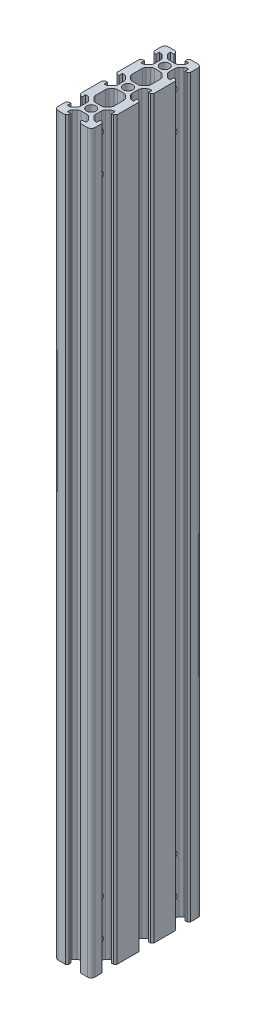
SolidWorks part; units mm, degrees
ref_plane "Front Plane" through (0, 0, 0) normal (0, 0, 1) x (1, 0, 0)
ref_plane "Top Plane" through (0, 0, 0) normal (0, 1, 0) x (1, 0, 0)
ref_plane "Right Plane" through (0, 0, 0) normal (1, 0, 0) x (0, 0, -1)
sketch "Sketch1" plane through (0, 0, 0) normal (0, 1, 0) x (1, 0, 0)
  line B0 (13.1, 59) -> (14.1, 60)
  line B1 (19, 6.9) -> (20, 5.9)
  line B2 (14.4142, 15.8284) -> (13.1236, 14.5379)
  line B3 (20, 14.1) -> (19, 13.1)
  line B4 (15.8284, 5.5858) -> (14.5379, 6.8764)
  line B5 (17.2426, 5) -> (18, 5)
  line B6 (18, 6.9) -> (18, 5)
  line B7 (17.2426, 15) -> (18, 15)
  line B8 (8.2906, 13.9521) -> (11.7094, 13.9521)
  line B9 (18, 15) -> (18, 13.1)
  line B10 (18, 13.1) -> (19, 13.1)
  line B11 (18, 6.9) -> (19, 6.9)
  line B12 (13.9521, 11.7094) -> (13.9521, 8.2906)
  line B13 (6.8764, 14.5379) -> (5.5858, 15.8284)
  line B14 (20, 5.9) -> (20, 2)
  line B15 (14.5379, 13.1236) -> (15.8284, 14.4142)
  line B16 (6.9, 1) -> (5.9, 0)
  line B17 (18, 0) -> (14.1, 0)
  line B18 (14.1, 0) -> (13.1, 1)
  line B19 (5.5858, 4.1716) -> (6.8764, 5.4621)
  line B20 (5, 2.7574) -> (5, 2)
  line B21 (6.9, 2) -> (5, 2)
  line B22 (15, 2.7574) -> (15, 2)
  line B23 (15, 2) -> (13.1, 2)
  line B24 (13.1, 2) -> (13.1, 1)
  line B25 (6.9, 2) -> (6.9, 1)
  line B26 (11.7094, 6.0479) -> (8.2906, 6.0479)
  line B27 (5.9, 0) -> (2, 0)
  line B28 (13.1236, 5.4621) -> (14.4142, 4.1716)
  line B29 (1, 13.1) -> (0, 14.1)
  line B30 (0, 2) -> (0, 5.9)
  line B31 (0, 5.9) -> (1, 6.9)
  line B32 (4.1716, 14.4142) -> (5.4621, 13.1236)
  line B33 (2.7574, 15) -> (2, 15)
  line B34 (2, 13.1) -> (2, 15)
  line B35 (2.7574, 5) -> (2, 5)
  line B36 (2, 5) -> (2, 6.9)
  line B37 (2, 6.9) -> (1, 6.9)
  line B38 (2, 13.1) -> (1, 13.1)
  line B39 (6.0479, 8.2906) -> (6.0479, 11.7094)
  line B40 (5.4621, 6.8764) -> (4.1716, 5.5858)
  circle B41 centre (10, 10) radius 2.5
  arc B42 (5.4621, 13.1236) -> (6.0479, 11.7094) centre (4.0479, 11.7094) cw
  arc B43 (4.1716, 14.4142) -> (2.7574, 15) centre (2.7574, 13) ccw
  arc B44 (5, 17.2426) -> (5.5858, 15.8284) centre (7, 17.2426) ccw
  arc B45 (15, 17.2426) -> (14.4142, 15.8284) centre (13, 17.2426) cw
  arc B46 (17.2426, 15) -> (15.8284, 14.4142) centre (17.2426, 13) ccw
  arc B47 (15.8284, 5.5858) -> (17.2426, 5) centre (17.2426, 7) ccw
  arc B48 (15, 2.7574) -> (14.4142, 4.1716) centre (13, 2.7574) ccw
  arc B49 (5.5858, 4.1716) -> (5, 2.7574) centre (7, 2.7574) ccw
  arc B50 (2.7574, 5) -> (4.1716, 5.5858) centre (2.7574, 7) ccw
  arc B51 (6.0479, 8.2906) -> (5.4621, 6.8764) centre (4.0479, 8.2906) cw
  arc B52 (6.8764, 5.4621) -> (8.2906, 6.0479) centre (8.2906, 4.0479) cw
  arc B53 (11.7094, 6.0479) -> (13.1236, 5.4621) centre (11.7094, 4.0479) cw
  arc B54 (14.5379, 6.8764) -> (13.9521, 8.2906) centre (15.9521, 8.2906) cw
  arc B55 (13.9521, 11.7094) -> (14.5379, 13.1236) centre (15.9521, 11.7094) cw
  arc B56 (11.7094, 13.9521) -> (13.1236, 14.5379) centre (11.7094, 15.9521) ccw
  arc B57 (8.2906, 13.9521) -> (6.8764, 14.5379) centre (8.2906, 15.9521) cw
  arc B58 (2, 0) -> (0, 2) centre (2, 2) cw
  arc B59 (20, 2) -> (18, 0) centre (18, 2) cw
  line B60 (19, 26.9) -> (20, 25.9)
  line B61 (15, 37.2426) -> (15, 42.7574)
  line B62 (14.4142, 35.8284) -> (13.1236, 34.5379)
  line B63 (18, 35) -> (18, 33.1)
  line B64 (20, 45.9) -> (20, 34.1)
  line B65 (0, 25.9) -> (1, 26.9)
  line B66 (17.2426, 25) -> (18, 25)
  line B67 (18, 26.9) -> (19, 26.9)
  line B68 (2, 26.9) -> (1, 26.9)
  line B69 (20, 34.1) -> (19, 33.1)
  line B70 (5, 22.7574) -> (5, 17.2426)
  line B71 (0, 34.1) -> (0, 45.9)
  line B72 (5, 37.2426) -> (5, 42.7574)
  line B73 (13.1236, 25.4621) -> (14.4142, 24.1716)
  line B74 (2, 25) -> (2, 26.9)
  line B75 (6.0479, 28.2906) -> (6.0479, 31.7094)
  line B76 (18, 33.1) -> (19, 33.1)
  line B77 (2, 33.1) -> (2, 35)
  line B78 (18, 26.9) -> (18, 25)
  line B79 (11.7094, 26.0479) -> (8.2906, 26.0479)
  line B80 (17.2426, 35) -> (18, 35)
  line B81 (20, 25.9) -> (20, 14.1)
  line B82 (1, 33.1) -> (0, 34.1)
  line B83 (14.5379, 33.1236) -> (15.8284, 34.4142)
  line B84 (4.1716, 34.4142) -> (5.4621, 33.1236)
  line B85 (13.9521, 31.7094) -> (13.9521, 28.2906)
  line B86 (2.7574, 35) -> (2, 35)
  line B87 (8.2906, 33.9521) -> (11.7094, 33.9521)
  line B88 (5.4621, 26.8764) -> (4.1716, 25.5858)
  line B89 (0, 14.1) -> (0, 25.9)
  line B90 (5.5858, 24.1716) -> (6.8764, 25.4621)
  line B91 (15.8284, 25.5858) -> (14.5379, 26.8764)
  line B92 (6.8764, 34.5379) -> (5.5858, 35.8284)
  line B93 (15, 22.7574) -> (15, 17.2426)
  line B94 (2.7574, 25) -> (2, 25)
  line B95 (2, 33.1) -> (1, 33.1)
  arc B96 (11.7094, 26.0479) -> (13.1236, 25.4621) centre (11.7094, 24.0479) cw
  arc B97 (13.9521, 31.7094) -> (14.5379, 33.1236) centre (15.9521, 31.7094) cw
  arc B98 (14.5379, 26.8764) -> (13.9521, 28.2906) centre (15.9521, 28.2906) cw
  arc B99 (5.5858, 24.1716) -> (5, 22.7574) centre (7, 22.7574) ccw
  arc B100 (5, 37.2426) -> (5.5858, 35.8284) centre (7, 37.2426) ccw
  arc B101 (11.7094, 33.9521) -> (13.1236, 34.5379) centre (11.7094, 35.9521) ccw
  arc B102 (15, 22.7574) -> (14.4142, 24.1716) centre (13, 22.7574) ccw
  arc B103 (2.7574, 25) -> (4.1716, 25.5858) centre (2.7574, 27) ccw
  arc B104 (15, 37.2426) -> (14.4142, 35.8284) centre (13, 37.2426) cw
  circle B105 centre (10, 30) radius 2.5
  arc B106 (8.2906, 33.9521) -> (6.8764, 34.5379) centre (8.2906, 35.9521) cw
  arc B107 (6.0479, 28.2906) -> (5.4621, 26.8764) centre (4.0479, 28.2906) cw
  arc B108 (6.8764, 25.4621) -> (8.2906, 26.0479) centre (8.2906, 24.0479) cw
  arc B109 (4.1716, 34.4142) -> (2.7574, 35) centre (2.7574, 33) ccw
  arc B110 (15.8284, 25.5858) -> (17.2426, 25) centre (17.2426, 27) ccw
  arc B111 (5.4621, 33.1236) -> (6.0479, 31.7094) centre (4.0479, 31.7094) cw
  arc B112 (17.2426, 35) -> (15.8284, 34.4142) centre (17.2426, 33) ccw
  line B113 (18, 55) -> (18, 53.1)
  line B114 (13.9521, 51.7094) -> (13.9521, 48.2906)
  line B115 (5.9, 60) -> (6.9, 59)
  line B116 (5, 57.2426) -> (5, 58)
  line B117 (4.1716, 54.4142) -> (5.4621, 53.1236)
  line B118 (18, 46.9) -> (19, 46.9)
  line B119 (13.1, 58) -> (13.1, 59)
  line B120 (11.7094, 46.0479) -> (8.2906, 46.0479)
  line B121 (2, 46.9) -> (1, 46.9)
  line B122 (6.8764, 54.5379) -> (5.5858, 55.8284)
  line B123 (13.1, 58) -> (15, 58)
  line B124 (2, 53.1) -> (2, 55)
  line B125 (18, 46.9) -> (18, 45)
  line B126 (0, 45.9) -> (1, 46.9)
  line B127 (6.9, 58) -> (6.9, 59)
  line B128 (13.1236, 45.4621) -> (14.4142, 44.1716)
  line B129 (15.8284, 45.5858) -> (14.5379, 46.8764)
  line B130 (20, 58) -> (20, 54.1)
  line B131 (2, 45) -> (2, 46.9)
  line B132 (17.2426, 55) -> (18, 55)
  line B133 (5, 58) -> (6.9, 58)
  line B134 (15, 57.2426) -> (15, 58)
  line B135 (2.7574, 45) -> (2, 45)
  line B136 (19, 46.9) -> (20, 45.9)
  line B137 (1, 53.1) -> (0, 54.1)
  line B138 (14.5379, 53.1236) -> (15.8284, 54.4142)
  line B139 (5.5858, 44.1716) -> (6.8764, 45.4621)
  line B140 (14.4142, 55.8284) -> (13.1236, 54.5379)
  line B141 (6.0479, 48.2906) -> (6.0479, 51.7094)
  line B142 (14.1, 60) -> (18, 60)
  line B143 (2, 60) -> (5.9, 60)
  line B144 (20, 54.1) -> (19, 53.1)
  line B145 (8.2906, 53.9521) -> (11.7094, 53.9521)
  line B146 (17.2426, 45) -> (18, 45)
  line B147 (0, 54.1) -> (0, 58)
  line B148 (2.7574, 55) -> (2, 55)
  line B149 (2, 53.1) -> (1, 53.1)
  line B150 (18, 53.1) -> (19, 53.1)
  line B151 (5.4621, 46.8764) -> (4.1716, 45.5858)
  arc B152 (5, 57.2426) -> (5.5858, 55.8284) centre (7, 57.2426) ccw
  arc B153 (2.7574, 45) -> (4.1716, 45.5858) centre (2.7574, 47) ccw
  arc B154 (11.7094, 46.0479) -> (13.1236, 45.4621) centre (11.7094, 44.0479) cw
  arc B155 (5.5858, 44.1716) -> (5, 42.7574) centre (7, 42.7574) ccw
  arc B156 (11.7094, 53.9521) -> (13.1236, 54.5379) centre (11.7094, 55.9521) ccw
  circle B157 centre (10, 50) radius 2.5
  arc B158 (0, 58) -> (2, 60) centre (2, 58) cw
  arc B159 (14.5379, 46.8764) -> (13.9521, 48.2906) centre (15.9521, 48.2906) cw
  arc B160 (6.8764, 45.4621) -> (8.2906, 46.0479) centre (8.2906, 44.0479) cw
  arc B161 (15, 57.2426) -> (14.4142, 55.8284) centre (13, 57.2426) cw
  arc B162 (15, 42.7574) -> (14.4142, 44.1716) centre (13, 42.7574) ccw
  arc B163 (5.4621, 53.1236) -> (6.0479, 51.7094) centre (4.0479, 51.7094) cw
  arc B164 (18, 60) -> (20, 58) centre (18, 58) cw
  arc B165 (6.0479, 48.2906) -> (5.4621, 46.8764) centre (4.0479, 48.2906) cw
  arc B166 (13.9521, 51.7094) -> (14.5379, 53.1236) centre (15.9521, 51.7094) cw
  arc B167 (4.1716, 54.4142) -> (2.7574, 55) centre (2.7574, 53) ccw
  arc B168 (8.2906, 53.9521) -> (6.8764, 54.5379) centre (8.2906, 55.9521) cw
  arc B169 (15.8284, 45.5858) -> (17.2426, 45) centre (17.2426, 47) ccw
  arc B170 (17.2426, 55) -> (15.8284, 54.4142) centre (17.2426, 53) ccw
sketch_block_instance "2060-1"
sketch_block "2060" parameters "D1"=2, "D2"=2, "D3"=2
extrude "Boss-Extrude1" add sketch "Sketch1" along normal blind 400
sketch "Sketch3" plane through (0, 0, 0) normal (-1, 0, 0) x (0, 0, 1)
  line L0 (-50, 400) -> (-50, 390) construction
  line L1 (-51.7094, 400) -> (-48.2906, 400) construction
  line L2 (-10, 400) -> (-10, 390) construction
  line L3 (-11.7094, 400) -> (-8.2906, 400) construction
  line L4 (-50, 390) -> (-50, 370) construction
  line L5 (-10, 390) -> (-10, 370) construction
  line L6 (0, 200) -> (53.5094, 200) construction
  line L7 (0, 400) -> (0, 0) construction
  line L8 (-10, 10) -> (-10, 30) construction
  line L9 (-50, 10) -> (-50, 30) construction
  line L10 (-10, 0) -> (-10, 10) construction
  line L11 (-50, 0) -> (-50, 10) construction
  circle A0 centre (-50, 390) radius 2.5
  circle A1 centre (-10, 390) radius 2.5
  circle A2 centre (-50, 370) radius 2.5
  circle A3 centre (-10, 370) radius 2.5
  circle A4 centre (-10, 30) radius 2.5
  circle A5 centre (-50, 30) radius 2.5
  circle A6 centre (-10, 10) radius 2.5
  circle A7 centre (-50, 10) radius 2.5
extrude "Cut-Extrude1" cut sketch "Sketch3" against normal through all
sketch "Sketch4" plane through (0, 0, 0) normal (-1, 0, 0) x (0, 0, 1)
  line L0 (0, 200) -> (53.5094, 200) construction
  line L1 (0, 200) -> (53.5094, 200) construction
  circle A0 centre (-50, 390) radius 5
  circle A1 centre (-50, 370) radius 5
  circle A2 centre (-10, 390) radius 5
  circle A3 centre (-10, 370) radius 5
  circle A4 centre (-10, 30) radius 5
  circle A5 centre (-10, 10) radius 5
  circle A6 centre (-50, 30) radius 5
  circle A7 centre (-50, 10) radius 5
sketch "Sketch5" plane through (0, 400, 0) normal (0, 1, 0) x (1, 0, 0)
  line B0 (13.1, 59) -> (14.1, 60)
  line B1 (19, 6.9) -> (20, 5.9)
  line B2 (14.4142, 15.8284) -> (13.1236, 14.5379)
  line B3 (20, 14.1) -> (19, 13.1)
  line B4 (15.8284, 5.5858) -> (14.5379, 6.8764)
  line B5 (17.2426, 5) -> (18, 5)
  line B6 (18, 6.9) -> (18, 5)
  line B7 (17.2426, 15) -> (18, 15)
  line B8 (8.2906, 13.9521) -> (11.7094, 13.9521)
  line B9 (18, 15) -> (18, 13.1)
  line B10 (18, 13.1) -> (19, 13.1)
  line B11 (18, 6.9) -> (19, 6.9)
  line B12 (13.9521, 11.7094) -> (13.9521, 8.2906)
  line B13 (6.8764, 14.5379) -> (5.5858, 15.8284)
  line B14 (20, 5.9) -> (20, 2)
  line B15 (14.5379, 13.1236) -> (15.8284, 14.4142)
  line B16 (6.9, 1) -> (5.9, 0)
  line B17 (18, 0) -> (14.1, 0)
  line B18 (14.1, 0) -> (13.1, 1)
  line B19 (5.5858, 4.1716) -> (6.8764, 5.4621)
  line B20 (5, 2.7574) -> (5, 2)
  line B21 (6.9, 2) -> (5, 2)
  line B22 (15, 2.7574) -> (15, 2)
  line B23 (15, 2) -> (13.1, 2)
  line B24 (13.1, 2) -> (13.1, 1)
  line B25 (6.9, 2) -> (6.9, 1)
  line B26 (11.7094, 6.0479) -> (8.2906, 6.0479)
  line B27 (5.9, 0) -> (2, 0)
  line B28 (13.1236, 5.4621) -> (14.4142, 4.1716)
  line B29 (1, 13.1) -> (0, 14.1)
  line B30 (0, 2) -> (0, 5.9)
  line B31 (0, 5.9) -> (1, 6.9)
  line B32 (4.1716, 14.4142) -> (5.4621, 13.1236)
  line B33 (2.7574, 15) -> (2, 15)
  line B34 (2, 13.1) -> (2, 15)
  line B35 (2.7574, 5) -> (2, 5)
  line B36 (2, 5) -> (2, 6.9)
  line B37 (2, 6.9) -> (1, 6.9)
  line B38 (2, 13.1) -> (1, 13.1)
  line B39 (6.0479, 8.2906) -> (6.0479, 11.7094)
  line B40 (5.4621, 6.8764) -> (4.1716, 5.5858)
  circle B41 centre (10, 10) radius 2.5
  arc B42 (5.4621, 13.1236) -> (6.0479, 11.7094) centre (4.0479, 11.7094) cw
  arc B43 (4.1716, 14.4142) -> (2.7574, 15) centre (2.7574, 13) ccw
  arc B44 (5, 17.2426) -> (5.5858, 15.8284) centre (7, 17.2426) ccw
  arc B45 (15, 17.2426) -> (14.4142, 15.8284) centre (13, 17.2426) cw
  arc B46 (17.2426, 15) -> (15.8284, 14.4142) centre (17.2426, 13) ccw
  arc B47 (15.8284, 5.5858) -> (17.2426, 5) centre (17.2426, 7) ccw
  arc B48 (15, 2.7574) -> (14.4142, 4.1716) centre (13, 2.7574) ccw
  arc B49 (5.5858, 4.1716) -> (5, 2.7574) centre (7, 2.7574) ccw
  arc B50 (2.7574, 5) -> (4.1716, 5.5858) centre (2.7574, 7) ccw
  arc B51 (6.0479, 8.2906) -> (5.4621, 6.8764) centre (4.0479, 8.2906) cw
  arc B52 (6.8764, 5.4621) -> (8.2906, 6.0479) centre (8.2906, 4.0479) cw
  arc B53 (11.7094, 6.0479) -> (13.1236, 5.4621) centre (11.7094, 4.0479) cw
  arc B54 (14.5379, 6.8764) -> (13.9521, 8.2906) centre (15.9521, 8.2906) cw
  arc B55 (13.9521, 11.7094) -> (14.5379, 13.1236) centre (15.9521, 11.7094) cw
  arc B56 (11.7094, 13.9521) -> (13.1236, 14.5379) centre (11.7094, 15.9521) ccw
  arc B57 (8.2906, 13.9521) -> (6.8764, 14.5379) centre (8.2906, 15.9521) cw
  arc B58 (2, 0) -> (0, 2) centre (2, 2) cw
  arc B59 (20, 2) -> (18, 0) centre (18, 2) cw
  line B60 (19, 26.9) -> (20, 25.9)
  line B61 (15, 37.2426) -> (15, 42.7574)
  line B62 (14.4142, 35.8284) -> (13.1236, 34.5379)
  line B63 (18, 35) -> (18, 33.1)
  line B64 (20, 45.9) -> (20, 34.1)
  line B65 (0, 25.9) -> (1, 26.9)
  line B66 (17.2426, 25) -> (18, 25)
  line B67 (18, 26.9) -> (19, 26.9)
  line B68 (2, 26.9) -> (1, 26.9)
  line B69 (20, 34.1) -> (19, 33.1)
  line B70 (5, 22.7574) -> (5, 17.2426)
  line B71 (0, 34.1) -> (0, 45.9)
  line B72 (5, 37.2426) -> (5, 42.7574)
  line B73 (13.1236, 25.4621) -> (14.4142, 24.1716)
  line B74 (2, 25) -> (2, 26.9)
  line B75 (6.0479, 28.2906) -> (6.0479, 31.7094)
  line B76 (18, 33.1) -> (19, 33.1)
  line B77 (2, 33.1) -> (2, 35)
  line B78 (18, 26.9) -> (18, 25)
  line B79 (11.7094, 26.0479) -> (8.2906, 26.0479)
  line B80 (17.2426, 35) -> (18, 35)
  line B81 (20, 25.9) -> (20, 14.1)
  line B82 (1, 33.1) -> (0, 34.1)
  line B83 (14.5379, 33.1236) -> (15.8284, 34.4142)
  line B84 (4.1716, 34.4142) -> (5.4621, 33.1236)
  line B85 (13.9521, 31.7094) -> (13.9521, 28.2906)
  line B86 (2.7574, 35) -> (2, 35)
  line B87 (8.2906, 33.9521) -> (11.7094, 33.9521)
  line B88 (5.4621, 26.8764) -> (4.1716, 25.5858)
  line B89 (0, 14.1) -> (0, 25.9)
  line B90 (5.5858, 24.1716) -> (6.8764, 25.4621)
  line B91 (15.8284, 25.5858) -> (14.5379, 26.8764)
  line B92 (6.8764, 34.5379) -> (5.5858, 35.8284)
  line B93 (15, 22.7574) -> (15, 17.2426)
  line B94 (2.7574, 25) -> (2, 25)
  line B95 (2, 33.1) -> (1, 33.1)
  arc B96 (11.7094, 26.0479) -> (13.1236, 25.4621) centre (11.7094, 24.0479) cw
  arc B97 (13.9521, 31.7094) -> (14.5379, 33.1236) centre (15.9521, 31.7094) cw
  arc B98 (14.5379, 26.8764) -> (13.9521, 28.2906) centre (15.9521, 28.2906) cw
  arc B99 (5.5858, 24.1716) -> (5, 22.7574) centre (7, 22.7574) ccw
  arc B100 (5, 37.2426) -> (5.5858, 35.8284) centre (7, 37.2426) ccw
  arc B101 (11.7094, 33.9521) -> (13.1236, 34.5379) centre (11.7094, 35.9521) ccw
  arc B102 (15, 22.7574) -> (14.4142, 24.1716) centre (13, 22.7574) ccw
  arc B103 (2.7574, 25) -> (4.1716, 25.5858) centre (2.7574, 27) ccw
  arc B104 (15, 37.2426) -> (14.4142, 35.8284) centre (13, 37.2426) cw
  circle B105 centre (10, 30) radius 2.5
  arc B106 (8.2906, 33.9521) -> (6.8764, 34.5379) centre (8.2906, 35.9521) cw
  arc B107 (6.0479, 28.2906) -> (5.4621, 26.8764) centre (4.0479, 28.2906) cw
  arc B108 (6.8764, 25.4621) -> (8.2906, 26.0479) centre (8.2906, 24.0479) cw
  arc B109 (4.1716, 34.4142) -> (2.7574, 35) centre (2.7574, 33) ccw
  arc B110 (15.8284, 25.5858) -> (17.2426, 25) centre (17.2426, 27) ccw
  arc B111 (5.4621, 33.1236) -> (6.0479, 31.7094) centre (4.0479, 31.7094) cw
  arc B112 (17.2426, 35) -> (15.8284, 34.4142) centre (17.2426, 33) ccw
  line B113 (18, 55) -> (18, 53.1)
  line B114 (13.9521, 51.7094) -> (13.9521, 48.2906)
  line B115 (5.9, 60) -> (6.9, 59)
  line B116 (5, 57.2426) -> (5, 58)
  line B117 (4.1716, 54.4142) -> (5.4621, 53.1236)
  line B118 (18, 46.9) -> (19, 46.9)
  line B119 (13.1, 58) -> (13.1, 59)
  line B120 (11.7094, 46.0479) -> (8.2906, 46.0479)
  line B121 (2, 46.9) -> (1, 46.9)
  line B122 (6.8764, 54.5379) -> (5.5858, 55.8284)
  line B123 (13.1, 58) -> (15, 58)
  line B124 (2, 53.1) -> (2, 55)
  line B125 (18, 46.9) -> (18, 45)
  line B126 (0, 45.9) -> (1, 46.9)
  line B127 (6.9, 58) -> (6.9, 59)
  line B128 (13.1236, 45.4621) -> (14.4142, 44.1716)
  line B129 (15.8284, 45.5858) -> (14.5379, 46.8764)
  line B130 (20, 58) -> (20, 54.1)
  line B131 (2, 45) -> (2, 46.9)
  line B132 (17.2426, 55) -> (18, 55)
  line B133 (5, 58) -> (6.9, 58)
  line B134 (15, 57.2426) -> (15, 58)
  line B135 (2.7574, 45) -> (2, 45)
  line B136 (19, 46.9) -> (20, 45.9)
  line B137 (1, 53.1) -> (0, 54.1)
  line B138 (14.5379, 53.1236) -> (15.8284, 54.4142)
  line B139 (5.5858, 44.1716) -> (6.8764, 45.4621)
  line B140 (14.4142, 55.8284) -> (13.1236, 54.5379)
  line B141 (6.0479, 48.2906) -> (6.0479, 51.7094)
  line B142 (14.1, 60) -> (18, 60)
  line B143 (2, 60) -> (5.9, 60)
  line B144 (20, 54.1) -> (19, 53.1)
  line B145 (8.2906, 53.9521) -> (11.7094, 53.9521)
  line B146 (17.2426, 45) -> (18, 45)
  line B147 (0, 54.1) -> (0, 58)
  line B148 (2.7574, 55) -> (2, 55)
  line B149 (2, 53.1) -> (1, 53.1)
  line B150 (18, 53.1) -> (19, 53.1)
  line B151 (5.4621, 46.8764) -> (4.1716, 45.5858)
  arc B152 (5, 57.2426) -> (5.5858, 55.8284) centre (7, 57.2426) ccw
  arc B153 (2.7574, 45) -> (4.1716, 45.5858) centre (2.7574, 47) ccw
  arc B154 (11.7094, 46.0479) -> (13.1236, 45.4621) centre (11.7094, 44.0479) cw
  arc B155 (5.5858, 44.1716) -> (5, 42.7574) centre (7, 42.7574) ccw
  arc B156 (11.7094, 53.9521) -> (13.1236, 54.5379) centre (11.7094, 55.9521) ccw
  circle B157 centre (10, 50) radius 2.5
  arc B158 (0, 58) -> (2, 60) centre (2, 58) cw
  arc B159 (14.5379, 46.8764) -> (13.9521, 48.2906) centre (15.9521, 48.2906) cw
  arc B160 (6.8764, 45.4621) -> (8.2906, 46.0479) centre (8.2906, 44.0479) cw
  arc B161 (15, 57.2426) -> (14.4142, 55.8284) centre (13, 57.2426) cw
  arc B162 (15, 42.7574) -> (14.4142, 44.1716) centre (13, 42.7574) ccw
  arc B163 (5.4621, 53.1236) -> (6.0479, 51.7094) centre (4.0479, 51.7094) cw
  arc B164 (18, 60) -> (20, 58) centre (18, 58) cw
  arc B165 (6.0479, 48.2906) -> (5.4621, 46.8764) centre (4.0479, 48.2906) cw
  arc B166 (13.9521, 51.7094) -> (14.5379, 53.1236) centre (15.9521, 51.7094) cw
  arc B167 (4.1716, 54.4142) -> (2.7574, 55) centre (2.7574, 53) ccw
  arc B168 (8.2906, 53.9521) -> (6.8764, 54.5379) centre (8.2906, 55.9521) cw
  arc B169 (15.8284, 45.5858) -> (17.2426, 45) centre (17.2426, 47) ccw
  arc B170 (17.2426, 55) -> (15.8284, 54.4142) centre (17.2426, 53) ccw
sketch_block_instance "2060-2"
sketch "Sketch6" plane through (0, 0, 0) normal (0, -1, 0) x (1, 0, 0)
  line L0 (5, -22.7574) -> (5, -17.2426) construction
  line L1 (6.8764, -14.5379) -> (5.5858, -15.8284) construction
  line L2 (8.2906, -13.9521) -> (11.7094, -13.9521) construction
  line L3 (14.4142, -15.8284) -> (13.1236, -14.5379) construction
  line L4 (15, -22.7574) -> (15, -17.2426) construction
  line L5 (13.1236, -25.4621) -> (14.4142, -24.1716) construction
  line L6 (11.7094, -26.0479) -> (8.2906, -26.0479) construction
  line L7 (5.5858, -24.1716) -> (6.8764, -25.4621) construction
  line L8 (11.7094, -46.0479) -> (8.2906, -46.0479) construction
  line L9 (5.5858, -44.1716) -> (6.8764, -45.4621) construction
  line L10 (5, -37.2426) -> (5, -42.7574) construction
  line L11 (6.8764, -34.5379) -> (5.5858, -35.8284) construction
  line L12 (8.2906, -33.9521) -> (11.7094, -33.9521) construction
  line L13 (14.4142, -35.8284) -> (13.1236, -34.5379) construction
  line L14 (15, -37.2426) -> (15, -42.7574) construction
  line L15 (13.1236, -45.4621) -> (14.4142, -44.1716) construction
  line L16 (13.9521, -51.7094) -> (13.9521, -48.2906) construction
  line L17 (15.8284, -45.5858) -> (14.5379, -46.8764) construction
  line L18 (17.2426, -45) -> (18, -45) construction
  line L19 (18, -46.9) -> (18, -45) construction
  line L20 (18, -46.9) -> (19, -46.9) construction
  line L21 (19, -46.9) -> (20, -45.9) construction
  line L22 (20, -45.9) -> (20, -34.1) construction
  line L23 (20, -34.1) -> (19, -33.1) construction
  line L24 (18, -33.1) -> (19, -33.1) construction
  line L25 (18, -35) -> (18, -33.1) construction
  line L26 (17.2426, -35) -> (18, -35) construction
  line L27 (14.5379, -33.1236) -> (15.8284, -34.4142) construction
  line L28 (13.9521, -31.7094) -> (13.9521, -28.2906) construction
  line L29 (15.8284, -25.5858) -> (14.5379, -26.8764) construction
  line L30 (17.2426, -25) -> (18, -25) construction
  line L31 (18, -26.9) -> (18, -25) construction
  line L32 (18, -26.9) -> (19, -26.9) construction
  line L33 (19, -26.9) -> (20, -25.9) construction
  line L34 (20, -25.9) -> (20, -14.1) construction
  line L35 (20, -14.1) -> (19, -13.1) construction
  line L36 (18, -13.1) -> (19, -13.1) construction
  line L37 (18, -15) -> (18, -13.1) construction
  line L38 (17.2426, -15) -> (18, -15) construction
  line L39 (14.5379, -13.1236) -> (15.8284, -14.4142) construction
  line L40 (13.9521, -11.7094) -> (13.9521, -8.2906) construction
  line L41 (15.8284, -5.5858) -> (14.5379, -6.8764) construction
  line L42 (17.2426, -5) -> (18, -5) construction
  line L43 (18, -6.9) -> (18, -5) construction
  line L44 (18, -6.9) -> (19, -6.9) construction
  line L45 (19, -6.9) -> (20, -5.9) construction
  line L46 (20, -5.9) -> (20, -2) construction
  line L47 (18, 0) -> (14.1, 0) construction
  line L48 (14.1, 0) -> (13.1, -1) construction
  line L49 (13.1, -2) -> (13.1, -1) construction
  line L50 (15, -2) -> (13.1, -2) construction
  line L51 (15, -2.7574) -> (15, -2) construction
  line L52 (13.1236, -5.4621) -> (14.4142, -4.1716) construction
  line L53 (11.7094, -6.0479) -> (8.2906, -6.0479) construction
  line L54 (5.5858, -4.1716) -> (6.8764, -5.4621) construction
  line L55 (5, -2.7574) -> (5, -2) construction
  line L56 (6.9, -2) -> (5, -2) construction
  line L57 (6.9, -2) -> (6.9, -1) construction
  line L58 (6.9, -1) -> (5.9, 0) construction
  line L59 (5.9, 0) -> (2, 0) construction
  line L60 (0, -2) -> (0, -5.9) construction
  line L61 (0, -5.9) -> (1, -6.9) construction
  line L62 (2, -6.9) -> (1, -6.9) construction
  line L63 (2, -5) -> (2, -6.9) construction
  line L64 (2.7574, -5) -> (2, -5) construction
  line L65 (5.4621, -6.8764) -> (4.1716, -5.5858) construction
  line L66 (6.0479, -8.2906) -> (6.0479, -11.7094) construction
  line L67 (4.1716, -14.4142) -> (5.4621, -13.1236) construction
  line L68 (2.7574, -15) -> (2, -15) construction
  line L69 (2, -13.1) -> (2, -15) construction
  line L70 (2, -13.1) -> (1, -13.1) construction
  line L71 (1, -13.1) -> (0, -14.1) construction
  line L72 (0, -14.1) -> (0, -25.9) construction
  line L73 (0, -25.9) -> (1, -26.9) construction
  line L74 (2, -26.9) -> (1, -26.9) construction
  line L75 (2, -25) -> (2, -26.9) construction
  line L76 (2.7574, -25) -> (2, -25) construction
  line L77 (5.4621, -26.8764) -> (4.1716, -25.5858) construction
  line L78 (6.0479, -28.2906) -> (6.0479, -31.7094) construction
  line L79 (4.1716, -34.4142) -> (5.4621, -33.1236) construction
  line L80 (2.7574, -35) -> (2, -35) construction
  line L81 (2, -33.1) -> (2, -35) construction
  line L82 (2, -33.1) -> (1, -33.1) construction
  line L83 (1, -33.1) -> (0, -34.1) construction
  line L84 (0, -34.1) -> (0, -45.9) construction
  line L85 (0, -45.9) -> (1, -46.9) construction
  line L86 (2, -46.9) -> (1, -46.9) construction
  line L87 (2, -45) -> (2, -46.9) construction
  line L88 (2.7574, -45) -> (2, -45) construction
  line L89 (5.4621, -46.8764) -> (4.1716, -45.5858) construction
  line L90 (6.0479, -48.2906) -> (6.0479, -51.7094) construction
  line L91 (4.1716, -54.4142) -> (5.4621, -53.1236) construction
  line L92 (2.7574, -55) -> (2, -55) construction
  line L93 (2, -53.1) -> (2, -55) construction
  line L94 (2, -53.1) -> (1, -53.1) construction
  line L95 (1, -53.1) -> (0, -54.1) construction
  line L96 (0, -54.1) -> (0, -58) construction
  line L97 (2, -60) -> (5.9, -60) construction
  line L98 (5.9, -60) -> (6.9, -59) construction
  line L99 (6.9, -58) -> (6.9, -59) construction
  line L100 (5, -58) -> (6.9, -58) construction
  line L101 (5, -57.2426) -> (5, -58) construction
  line L102 (6.8764, -54.5379) -> (5.5858, -55.8284) construction
  line L103 (8.2906, -53.9521) -> (11.7094, -53.9521) construction
  line L104 (14.4142, -55.8284) -> (13.1236, -54.5379) construction
  line L105 (15, -57.2426) -> (15, -58) construction
  line L106 (13.1, -58) -> (15, -58) construction
  line L107 (13.1, -58) -> (13.1, -59) construction
  line L108 (13.1, -59) -> (14.1, -60) construction
  line L109 (14.1, -60) -> (18, -60) construction
  line L110 (20, -58) -> (20, -54.1) construction
  line L111 (20, -54.1) -> (19, -53.1) construction
  line L112 (18, -53.1) -> (19, -53.1) construction
  line L113 (18, -55) -> (18, -53.1) construction
  line L114 (17.2426, -55) -> (18, -55) construction
  line L115 (14.5379, -53.1236) -> (15.8284, -54.4142) construction
  line L116 (5, -22.7574) -> (5, -17.2426)
  line L117 (6.8764, -14.5379) -> (5.5858, -15.8284)
  line L118 (8.2906, -13.9521) -> (11.7094, -13.9521)
  line L119 (14.4142, -15.8284) -> (13.1236, -14.5379)
  line L120 (15, -22.7574) -> (15, -17.2426)
  line L121 (13.1236, -25.4621) -> (14.4142, -24.1716)
  line L122 (11.7094, -26.0479) -> (8.2906, -26.0479)
  line L123 (5.5858, -24.1716) -> (6.8764, -25.4621)
  line L124 (11.7094, -46.0479) -> (8.2906, -46.0479)
  line L125 (5.5858, -44.1716) -> (6.8764, -45.4621)
  line L126 (5, -37.2426) -> (5, -42.7574)
  line L127 (6.8764, -34.5379) -> (5.5858, -35.8284)
  line L128 (8.2906, -33.9521) -> (11.7094, -33.9521)
  line L129 (14.4142, -35.8284) -> (13.1236, -34.5379)
  line L130 (15, -37.2426) -> (15, -42.7574)
  line L131 (13.1236, -45.4621) -> (14.4142, -44.1716)
  line L132 (13.9521, -51.7094) -> (13.9521, -48.2906)
  line L133 (15.8284, -45.5858) -> (14.5379, -46.8764)
  line L134 (17.2426, -45) -> (18, -45)
  line L135 (18, -46.9) -> (18, -45)
  line L136 (18, -46.9) -> (19, -46.9)
  line L137 (19, -46.9) -> (20, -45.9)
  line L138 (20, -45.9) -> (20, -34.1)
  line L139 (20, -34.1) -> (19, -33.1)
  line L140 (18, -33.1) -> (19, -33.1)
  line L141 (18, -35) -> (18, -33.1)
  line L142 (17.2426, -35) -> (18, -35)
  line L143 (14.5379, -33.1236) -> (15.8284, -34.4142)
  line L144 (13.9521, -31.7094) -> (13.9521, -28.2906)
  line L145 (15.8284, -25.5858) -> (14.5379, -26.8764)
  line L146 (17.2426, -25) -> (18, -25)
  line L147 (18, -26.9) -> (18, -25)
  line L148 (18, -26.9) -> (19, -26.9)
  line L149 (19, -26.9) -> (20, -25.9)
  line L150 (20, -25.9) -> (20, -14.1)
  line L151 (20, -14.1) -> (19, -13.1)
  line L152 (18, -13.1) -> (19, -13.1)
  line L153 (18, -15) -> (18, -13.1)
  line L154 (17.2426, -15) -> (18, -15)
  line L155 (14.5379, -13.1236) -> (15.8284, -14.4142)
  line L156 (13.9521, -11.7094) -> (13.9521, -8.2906)
  line L157 (15.8284, -5.5858) -> (14.5379, -6.8764)
  line L158 (17.2426, -5) -> (18, -5)
  line L159 (18, -6.9) -> (18, -5)
  line L160 (18, -6.9) -> (19, -6.9)
  line L161 (19, -6.9) -> (20, -5.9)
  line L162 (20, -5.9) -> (20, -2)
  line L163 (18, 0) -> (14.1, 0)
  line L164 (14.1, 0) -> (13.1, -1)
  line L165 (13.1, -2) -> (13.1, -1)
  line L166 (15, -2) -> (13.1, -2)
  line L167 (15, -2.7574) -> (15, -2)
  line L168 (13.1236, -5.4621) -> (14.4142, -4.1716)
  line L169 (11.7094, -6.0479) -> (8.2906, -6.0479)
  line L170 (5.5858, -4.1716) -> (6.8764, -5.4621)
  line L171 (5, -2.7574) -> (5, -2)
  line L172 (6.9, -2) -> (5, -2)
  line L173 (6.9, -2) -> (6.9, -1)
  line L174 (6.9, -1) -> (5.9, 0)
  line L175 (5.9, 0) -> (2, 0)
  line L176 (0, -2) -> (0, -5.9)
  line L177 (0, -5.9) -> (1, -6.9)
  line L178 (2, -6.9) -> (1, -6.9)
  line L179 (2, -5) -> (2, -6.9)
  line L180 (2.7574, -5) -> (2, -5)
  line L181 (5.4621, -6.8764) -> (4.1716, -5.5858)
  line L182 (6.0479, -8.2906) -> (6.0479, -11.7094)
  line L183 (4.1716, -14.4142) -> (5.4621, -13.1236)
  line L184 (2.7574, -15) -> (2, -15)
  line L185 (2, -13.1) -> (2, -15)
  line L186 (2, -13.1) -> (1, -13.1)
  line L187 (1, -13.1) -> (0, -14.1)
  line L188 (0, -14.1) -> (0, -25.9)
  line L189 (0, -25.9) -> (1, -26.9)
  line L190 (2, -26.9) -> (1, -26.9)
  line L191 (2, -25) -> (2, -26.9)
  line L192 (2.7574, -25) -> (2, -25)
  line L193 (5.4621, -26.8764) -> (4.1716, -25.5858)
  line L194 (6.0479, -28.2906) -> (6.0479, -31.7094)
  line L195 (4.1716, -34.4142) -> (5.4621, -33.1236)
  line L196 (2.7574, -35) -> (2, -35)
  line L197 (2, -33.1) -> (2, -35)
  line L198 (2, -33.1) -> (1, -33.1)
  line L199 (1, -33.1) -> (0, -34.1)
  line L200 (0, -34.1) -> (0, -45.9)
  line L201 (0, -45.9) -> (1, -46.9)
  line L202 (2, -46.9) -> (1, -46.9)
  line L203 (2, -45) -> (2, -46.9)
  line L204 (2.7574, -45) -> (2, -45)
  line L205 (5.4621, -46.8764) -> (4.1716, -45.5858)
  line L206 (6.0479, -48.2906) -> (6.0479, -51.7094)
  line L207 (4.1716, -54.4142) -> (5.4621, -53.1236)
  line L208 (2.7574, -55) -> (2, -55)
  line L209 (2, -53.1) -> (2, -55)
  line L210 (2, -53.1) -> (1, -53.1)
  line L211 (1, -53.1) -> (0, -54.1)
  line L212 (0, -54.1) -> (0, -58)
  line L213 (2, -60) -> (5.9, -60)
  line L214 (5.9, -60) -> (6.9, -59)
  line L215 (6.9, -58) -> (6.9, -59)
  line L216 (5, -58) -> (6.9, -58)
  line L217 (5, -57.2426) -> (5, -58)
  line L218 (6.8764, -54.5379) -> (5.5858, -55.8284)
  line L219 (8.2906, -53.9521) -> (11.7094, -53.9521)
  line L220 (14.4142, -55.8284) -> (13.1236, -54.5379)
  line L221 (15, -57.2426) -> (15, -58)
  line L222 (13.1, -58) -> (15, -58)
  line L223 (13.1, -58) -> (13.1, -59)
  line L224 (13.1, -59) -> (14.1, -60)
  line L225 (14.1, -60) -> (18, -60)
  line L226 (20, -58) -> (20, -54.1)
  line L227 (20, -54.1) -> (19, -53.1)
  line L228 (18, -53.1) -> (19, -53.1)
  line L229 (18, -55) -> (18, -53.1)
  line L230 (17.2426, -55) -> (18, -55)
  line L231 (14.5379, -53.1236) -> (15.8284, -54.4142)
  circle A0 centre (10, -50) radius 2.5 construction
  circle A1 centre (10, -10) radius 2.5 construction
  circle A2 centre (10, -30) radius 2.5 construction
  arc A3 (5.5858, -15.8284) -> (5, -17.2426) centre (7, -17.2426) ccw construction
  arc A4 (8.2906, -13.9521) -> (6.8764, -14.5379) centre (8.2906, -15.9521) ccw construction
  arc A5 (13.1236, -14.5379) -> (11.7094, -13.9521) centre (11.7094, -15.9521) ccw construction
  arc A6 (15, -17.2426) -> (14.4142, -15.8284) centre (13, -17.2426) ccw construction
  arc A7 (14.4142, -24.1716) -> (15, -22.7574) centre (13, -22.7574) ccw construction
  arc A8 (11.7094, -26.0479) -> (13.1236, -25.4621) centre (11.7094, -24.0479) ccw construction
  arc A9 (6.8764, -25.4621) -> (8.2906, -26.0479) centre (8.2906, -24.0479) ccw construction
  arc A10 (5, -22.7574) -> (5.5858, -24.1716) centre (7, -22.7574) ccw construction
  arc A11 (6.8764, -45.4621) -> (8.2906, -46.0479) centre (8.2906, -44.0479) ccw construction
  arc A12 (5, -42.7574) -> (5.5858, -44.1716) centre (7, -42.7574) ccw construction
  arc A13 (5.5858, -35.8284) -> (5, -37.2426) centre (7, -37.2426) ccw construction
  arc A14 (8.2906, -33.9521) -> (6.8764, -34.5379) centre (8.2906, -35.9521) ccw construction
  arc A15 (13.1236, -34.5379) -> (11.7094, -33.9521) centre (11.7094, -35.9521) ccw construction
  arc A16 (15, -37.2426) -> (14.4142, -35.8284) centre (13, -37.2426) ccw construction
  arc A17 (14.4142, -44.1716) -> (15, -42.7574) centre (13, -42.7574) ccw construction
  arc A18 (11.7094, -46.0479) -> (13.1236, -45.4621) centre (11.7094, -44.0479) ccw construction
  arc A19 (14.5379, -46.8764) -> (13.9521, -48.2906) centre (15.9521, -48.2906) ccw construction
  arc A20 (17.2426, -45) -> (15.8284, -45.5858) centre (17.2426, -47) ccw construction
  arc A21 (15.8284, -34.4142) -> (17.2426, -35) centre (17.2426, -33) ccw construction
  arc A22 (13.9521, -31.7094) -> (14.5379, -33.1236) centre (15.9521, -31.7094) ccw construction
  arc A23 (14.5379, -26.8764) -> (13.9521, -28.2906) centre (15.9521, -28.2906) ccw construction
  arc A24 (17.2426, -25) -> (15.8284, -25.5858) centre (17.2426, -27) ccw construction
  arc A25 (15.8284, -14.4142) -> (17.2426, -15) centre (17.2426, -13) ccw construction
  arc A26 (13.9521, -11.7094) -> (14.5379, -13.1236) centre (15.9521, -11.7094) ccw construction
  arc A27 (14.5379, -6.8764) -> (13.9521, -8.2906) centre (15.9521, -8.2906) ccw construction
  arc A28 (17.2426, -5) -> (15.8284, -5.5858) centre (17.2426, -7) ccw construction
  arc A29 (20, -2) -> (18, 0) centre (18, -2) ccw construction
  arc A30 (14.4142, -4.1716) -> (15, -2.7574) centre (13, -2.7574) ccw construction
  arc A31 (11.7094, -6.0479) -> (13.1236, -5.4621) centre (11.7094, -4.0479) ccw construction
  arc A32 (6.8764, -5.4621) -> (8.2906, -6.0479) centre (8.2906, -4.0479) ccw construction
  arc A33 (5, -2.7574) -> (5.5858, -4.1716) centre (7, -2.7574) ccw construction
  arc A34 (2, 0) -> (0, -2) centre (2, -2) ccw construction
  arc A35 (4.1716, -5.5858) -> (2.7574, -5) centre (2.7574, -7) ccw construction
  arc A36 (6.0479, -8.2906) -> (5.4621, -6.8764) centre (4.0479, -8.2906) ccw construction
  arc A37 (5.4621, -13.1236) -> (6.0479, -11.7094) centre (4.0479, -11.7094) ccw construction
  arc A38 (2.7574, -15) -> (4.1716, -14.4142) centre (2.7574, -13) ccw construction
  arc A39 (4.1716, -25.5858) -> (2.7574, -25) centre (2.7574, -27) ccw construction
  arc A40 (6.0479, -28.2906) -> (5.4621, -26.8764) centre (4.0479, -28.2906) ccw construction
  arc A41 (5.4621, -33.1236) -> (6.0479, -31.7094) centre (4.0479, -31.7094) ccw construction
  arc A42 (2.7574, -35) -> (4.1716, -34.4142) centre (2.7574, -33) ccw construction
  arc A43 (4.1716, -45.5858) -> (2.7574, -45) centre (2.7574, -47) ccw construction
  arc A44 (6.0479, -48.2906) -> (5.4621, -46.8764) centre (4.0479, -48.2906) ccw construction
  arc A45 (5.4621, -53.1236) -> (6.0479, -51.7094) centre (4.0479, -51.7094) ccw construction
  arc A46 (2.7574, -55) -> (4.1716, -54.4142) centre (2.7574, -53) ccw construction
  arc A47 (0, -58) -> (2, -60) centre (2, -58) ccw construction
  arc A48 (5.5858, -55.8284) -> (5, -57.2426) centre (7, -57.2426) ccw construction
  arc A49 (8.2906, -53.9521) -> (6.8764, -54.5379) centre (8.2906, -55.9521) ccw construction
  arc A50 (13.1236, -54.5379) -> (11.7094, -53.9521) centre (11.7094, -55.9521) ccw construction
  arc A51 (15, -57.2426) -> (14.4142, -55.8284) centre (13, -57.2426) ccw construction
  arc A52 (18, -60) -> (20, -58) centre (18, -58) ccw construction
  arc A53 (15.8284, -54.4142) -> (17.2426, -55) centre (17.2426, -53) ccw construction
  arc A54 (13.9521, -51.7094) -> (14.5379, -53.1236) centre (15.9521, -51.7094) ccw construction
  circle A55 centre (10, -50) radius 2.5
  circle A56 centre (10, -10) radius 2.5
  circle A57 centre (10, -30) radius 2.5
  arc A58 (5.5858, -15.8284) -> (5, -17.2426) centre (7, -17.2426) ccw
  arc A59 (8.2906, -13.9521) -> (6.8764, -14.5379) centre (8.2906, -15.9521) ccw
  arc A60 (13.1236, -14.5379) -> (11.7094, -13.9521) centre (11.7094, -15.9521) ccw
  arc A61 (15, -17.2426) -> (14.4142, -15.8284) centre (13, -17.2426) ccw
  arc A62 (14.4142, -24.1716) -> (15, -22.7574) centre (13, -22.7574) ccw
  arc A63 (11.7094, -26.0479) -> (13.1236, -25.4621) centre (11.7094, -24.0479) ccw
  arc A64 (6.8764, -25.4621) -> (8.2906, -26.0479) centre (8.2906, -24.0479) ccw
  arc A65 (5, -22.7574) -> (5.5858, -24.1716) centre (7, -22.7574) ccw
  arc A66 (6.8764, -45.4621) -> (8.2906, -46.0479) centre (8.2906, -44.0479) ccw
  arc A67 (5, -42.7574) -> (5.5858, -44.1716) centre (7, -42.7574) ccw
  arc A68 (5.5858, -35.8284) -> (5, -37.2426) centre (7, -37.2426) ccw
  arc A69 (8.2906, -33.9521) -> (6.8764, -34.5379) centre (8.2906, -35.9521) ccw
  arc A70 (13.1236, -34.5379) -> (11.7094, -33.9521) centre (11.7094, -35.9521) ccw
  arc A71 (15, -37.2426) -> (14.4142, -35.8284) centre (13, -37.2426) ccw
  arc A72 (14.4142, -44.1716) -> (15, -42.7574) centre (13, -42.7574) ccw
  arc A73 (11.7094, -46.0479) -> (13.1236, -45.4621) centre (11.7094, -44.0479) ccw
  arc A74 (14.5379, -46.8764) -> (13.9521, -48.2906) centre (15.9521, -48.2906) ccw
  arc A75 (17.2426, -45) -> (15.8284, -45.5858) centre (17.2426, -47) ccw
  arc A76 (15.8284, -34.4142) -> (17.2426, -35) centre (17.2426, -33) ccw
  arc A77 (13.9521, -31.7094) -> (14.5379, -33.1236) centre (15.9521, -31.7094) ccw
  arc A78 (14.5379, -26.8764) -> (13.9521, -28.2906) centre (15.9521, -28.2906) ccw
  arc A79 (17.2426, -25) -> (15.8284, -25.5858) centre (17.2426, -27) ccw
  arc A80 (15.8284, -14.4142) -> (17.2426, -15) centre (17.2426, -13) ccw
  arc A81 (13.9521, -11.7094) -> (14.5379, -13.1236) centre (15.9521, -11.7094) ccw
  arc A82 (14.5379, -6.8764) -> (13.9521, -8.2906) centre (15.9521, -8.2906) ccw
  arc A83 (17.2426, -5) -> (15.8284, -5.5858) centre (17.2426, -7) ccw
  arc A84 (20, -2) -> (18, 0) centre (18, -2) ccw
  arc A85 (14.4142, -4.1716) -> (15, -2.7574) centre (13, -2.7574) ccw
  arc A86 (11.7094, -6.0479) -> (13.1236, -5.4621) centre (11.7094, -4.0479) ccw
  arc A87 (6.8764, -5.4621) -> (8.2906, -6.0479) centre (8.2906, -4.0479) ccw
  arc A88 (5, -2.7574) -> (5.5858, -4.1716) centre (7, -2.7574) ccw
  arc A89 (2, 0) -> (0, -2) centre (2, -2) ccw
  arc A90 (4.1716, -5.5858) -> (2.7574, -5) centre (2.7574, -7) ccw
  arc A91 (6.0479, -8.2906) -> (5.4621, -6.8764) centre (4.0479, -8.2906) ccw
  arc A92 (5.4621, -13.1236) -> (6.0479, -11.7094) centre (4.0479, -11.7094) ccw
  arc A93 (2.7574, -15) -> (4.1716, -14.4142) centre (2.7574, -13) ccw
  arc A94 (4.1716, -25.5858) -> (2.7574, -25) centre (2.7574, -27) ccw
  arc A95 (6.0479, -28.2906) -> (5.4621, -26.8764) centre (4.0479, -28.2906) ccw
  arc A96 (5.4621, -33.1236) -> (6.0479, -31.7094) centre (4.0479, -31.7094) ccw
  arc A97 (2.7574, -35) -> (4.1716, -34.4142) centre (2.7574, -33) ccw
  arc A98 (4.1716, -45.5858) -> (2.7574, -45) centre (2.7574, -47) ccw
  arc A99 (6.0479, -48.2906) -> (5.4621, -46.8764) centre (4.0479, -48.2906) ccw
  arc A100 (5.4621, -53.1236) -> (6.0479, -51.7094) centre (4.0479, -51.7094) ccw
  arc A101 (2.7574, -55) -> (4.1716, -54.4142) centre (2.7574, -53) ccw
  arc A102 (0, -58) -> (2, -60) centre (2, -58) ccw
  arc A103 (5.5858, -55.8284) -> (5, -57.2426) centre (7, -57.2426) ccw
  arc A104 (8.2906, -53.9521) -> (6.8764, -54.5379) centre (8.2906, -55.9521) ccw
  arc A105 (13.1236, -54.5379) -> (11.7094, -53.9521) centre (11.7094, -55.9521) ccw
  arc A106 (15, -57.2426) -> (14.4142, -55.8284) centre (13, -57.2426) ccw
  arc A107 (18, -60) -> (20, -58) centre (18, -58) ccw
  arc A108 (15.8284, -54.4142) -> (17.2426, -55) centre (17.2426, -53) ccw
  arc A109 (13.9521, -51.7094) -> (14.5379, -53.1236) centre (15.9521, -51.7094) ccw
